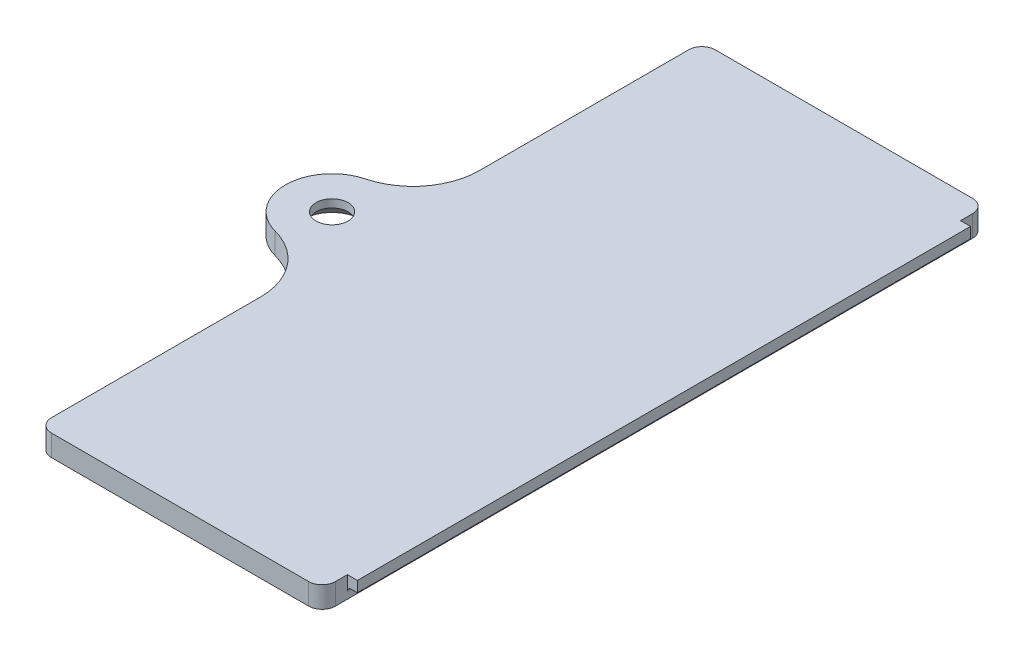
SolidWorks part; units mm, degrees
ref_plane "Front Plane" through (0, 0, 0) normal (0, 0, 1) x (1, 0, 0)
ref_plane "Top Plane" through (0, 0, 0) normal (0, 1, 0) x (1, 0, 0)
ref_plane "Right Plane" through (0, 0, 0) normal (1, 0, 0) x (0, 0, -1)
sketch "Door Plate 1.6 + screw ear (R5 / R3.5) Sketch" plane through (0, 0, 0) normal (0, 1, 0) x (1, 0, 0)
  line L0 (9.35, 15.1) -> (30.65, 15.1)
  line L1 (30.65, 15.1) -> (30.65, 64.9)
  line L2 (30.65, 64.9) -> (9.35, 64.9)
  line L3 (9.35, 64.9) -> (9.35, 48.2236)
  line L4 (9.35, 31.7764) -> (9.35, 15.1)
  arc A0 (9.35, 31.7764) -> (5.6147, 36.6138) centre (4.35, 31.7764) ccw
  arc A1 (5.6147, 36.6138) -> (5.6147, 43.3862) centre (6.5, 40) cw
  arc A2 (5.6147, 43.3862) -> (9.35, 48.2236) centre (4.35, 48.2236) ccw
extrude "Door Plate 1.6 + screw ear (R5 / R3.5)" add sketch "Door Plate 1.6 + screw ear (R5 / R3.5) Sketch" along normal blind 1.6
ref_plane "Hook Flange Plane y0.8" through (0, 0.8, 0) normal (0, 1, 0) x (1, 0, 0)
sketch "Hook Flange 0.75 x 0.8 (inner-face plane) Sketch" plane through (0, 0.8, 0) normal (0, 1, 0) x (1, 0, 0)
  line L0 (30.5, 17) -> (31.4, 17)
  line L1 (31.4, 17) -> (31.4, 63)
  line L2 (31.4, 63) -> (30.5, 63)
  line L3 (30.5, 63) -> (30.5, 17)
extrude "Hook Flange 0.75 x 0.8 (inner-face plane)" add sketch "Hook Flange 0.75 x 0.8 (inner-face plane) Sketch" along normal blind 0.8
sketch "Screw Hole 2.4 (free) Sketch" plane through (0, 0, 0) normal (0, 1, 0) x (1, 0, 0)
  circle A0 centre (6.5, 40) radius 1.2
extrude "Screw Hole 2.4 (free)" cut sketch "Screw Hole 2.4 (free) Sketch" along normal through all
chamfer "Screw CSK 90deg (M2)" distance 1 angle 45 1 edges at (6.5, 0, -38.8)
fillet "Door Corners R1 (print)" radius 1 4 edges at (9.35, 0.8, -64.9) (30.65, 0.8, -64.9) (30.65, 0.8, -15.1) (9.35, 0.8, -15.1)
fillet "Hook Flange Root Fillet R0.3" radius 0.3 1 edges at (30.65, 0.8, -40)
sketch "Door Text Slits 8160749347 + TIMER REMOTE (outer face, 0.84 stroke) Sketch" plane through (0, 0, 0) normal (0, 1, 0) x (1, 0, 0)
  line L0 (27.28, 17.22) -> (21.12, 17.22)
  line L1 (20.6, 17.74) -> (20.6, 20.5)
  line L2 (21.12, 21.02) -> (27.28, 21.02)
  line L3 (27.8, 20.5) -> (27.8, 17.74)
  line L4 (21.12, 17.32) -> (27.28, 17.32)
  line L5 (27.7, 17.74) -> (27.7, 20.5)
  line L6 (27.28, 20.92) -> (21.12, 20.92)
  line L7 (20.7, 20.5) -> (20.7, 17.74)
  line L8 (21.12, 24.28) -> (27.28, 24.28)
  line L9 (27.8, 23.76) -> (27.8, 22.76)
  line L10 (26.76, 22.76) -> (26.76, 23.24)
  line L11 (26.76, 23.24) -> (21.12, 23.24)
  line L12 (27.7, 23.76) -> (27.7, 22.76)
  line L13 (26.86, 22.76) -> (26.86, 23.34)
  line L14 (26.86, 23.34) -> (21.12, 23.34)
  line L15 (21.12, 24.18) -> (27.28, 24.18)
  line L16 (21.12, 30.3) -> (24.2, 30.3)
  line L17 (24.72, 29.78) -> (24.72, 27.54)
  line L18 (24.72, 27.54) -> (26.76, 27.54)
  line L19 (26.76, 27.54) -> (26.76, 29.78)
  line L20 (27.8, 29.78) -> (27.8, 27.02)
  line L21 (27.28, 26.5) -> (21.12, 26.5)
  line L22 (20.6, 27.02) -> (20.6, 29.78)
  line L23 (27.7, 29.78) -> (27.7, 27.02)
  line L24 (27.28, 26.6) -> (21.12, 26.6)
  line L25 (20.7, 27.02) -> (20.7, 29.78)
  line L26 (21.12, 30.2) -> (24.2, 30.2)
  line L27 (24.62, 29.78) -> (24.62, 27.44)
  line L28 (24.62, 27.44) -> (26.86, 27.44)
  line L29 (26.86, 27.44) -> (26.86, 29.78)
  line L30 (27.28, 31.14) -> (21.12, 31.14)
  line L31 (20.6, 31.66) -> (20.6, 34.42)
  line L32 (21.12, 34.94) -> (27.28, 34.94)
  line L33 (27.8, 34.42) -> (27.8, 31.66)
  line L34 (21.12, 31.24) -> (27.28, 31.24)
  line L35 (27.7, 31.66) -> (27.7, 34.42)
  line L36 (27.28, 34.84) -> (21.12, 34.84)
  line L37 (20.7, 34.42) -> (20.7, 31.66)
  line L38 (20.9832, 37.8817) -> (27.1432, 39.5617)
  line L39 (27.8, 39.06) -> (27.8, 36.3)
  line L40 (26.76, 36.3) -> (26.76, 38.3792)
  line L41 (26.76, 38.3792) -> (21.2568, 36.8783)
  line L42 (27.7, 39.06) -> (27.7, 36.3)
  line L43 (26.86, 36.3) -> (26.86, 38.5101)
  line L44 (26.86, 38.5101) -> (21.2305, 36.9748)
  line L45 (21.0095, 37.7852) -> (27.1695, 39.4652)
  line L46 (21.12, 44.22) -> (27.28, 44.22)
  line L47 (27.28, 43.18) -> (24.72, 43.18)
  line L48 (24.72, 43.18) -> (24.72, 41.46)
  line L49 (24.72, 41.46) -> (27.28, 41.46)
  line L50 (27.28, 40.42) -> (24.2, 40.42)
  line L51 (23.68, 40.94) -> (23.68, 43.18)
  line L52 (23.68, 43.18) -> (21.12, 43.18)
  line L53 (27.28, 40.52) -> (24.2, 40.52)
  line L54 (23.78, 40.94) -> (23.78, 43.28)
  line L55 (23.78, 43.28) -> (21.12, 43.28)
  line L56 (21.12, 44.12) -> (27.28, 44.12)
  line L57 (27.28, 43.28) -> (24.62, 43.28)
  line L58 (24.62, 43.28) -> (24.62, 41.36)
  line L59 (24.62, 41.36) -> (27.28, 41.36)
  line L60 (23.68, 47.82) -> (21.64, 47.82)
  line L61 (21.64, 47.82) -> (21.64, 45.58)
  line L62 (20.6, 45.58) -> (20.6, 48.34)
  line L63 (21.12, 48.86) -> (27.28, 48.86)
  line L64 (27.8, 48.34) -> (27.8, 45.58)
  line L65 (27.28, 45.06) -> (24.2, 45.06)
  line L66 (23.68, 45.58) -> (23.68, 47.82)
  line L67 (20.7, 48.34) -> (20.7, 45.58)
  line L68 (21.54, 45.58) -> (21.54, 47.92)
  line L69 (21.54, 47.92) -> (23.78, 47.92)
  line L70 (23.78, 47.92) -> (23.78, 45.58)
  line L71 (24.2, 45.16) -> (27.28, 45.16)
  line L72 (27.7, 45.58) -> (27.7, 48.34)
  line L73 (27.28, 48.76) -> (21.12, 48.76)
  line L74 (21.64, 52.46) -> (21.64, 50.22)
  line L75 (20.6, 50.22) -> (20.6, 52.98)
  line L76 (21.12, 53.5) -> (27.28, 53.5)
  line L77 (27.8, 52.98) -> (27.8, 50.22)
  line L78 (26.76, 50.22) -> (26.76, 52.46)
  line L79 (26.76, 52.46) -> (24.72, 52.46)
  line L80 (24.72, 52.46) -> (24.72, 51.02)
  line L81 (23.68, 51.02) -> (23.68, 52.46)
  line L82 (23.68, 52.46) -> (21.64, 52.46)
  line L83 (27.28, 53.4) -> (21.12, 53.4)
  line L84 (20.7, 52.98) -> (20.7, 50.22)
  line L85 (21.54, 50.22) -> (21.54, 52.56)
  line L86 (21.54, 52.56) -> (23.78, 52.56)
  line L87 (23.78, 52.56) -> (23.78, 51.02)
  line L88 (24.62, 51.02) -> (24.62, 52.56)
  line L89 (24.62, 52.56) -> (26.86, 52.56)
  line L90 (26.86, 52.56) -> (26.86, 50.22)
  line L91 (27.7, 50.22) -> (27.7, 52.98)
  line L92 (21.12, 58.14) -> (27.28, 58.14)
  line L93 (27.28, 57.1) -> (24.72, 57.1)
  line L94 (24.72, 57.1) -> (24.72, 55.38)
  line L95 (24.72, 55.38) -> (27.28, 55.38)
  line L96 (27.28, 54.34) -> (24.2, 54.34)
  line L97 (23.68, 54.86) -> (23.68, 57.1)
  line L98 (23.68, 57.1) -> (21.12, 57.1)
  line L99 (27.28, 54.44) -> (24.2, 54.44)
  line L100 (23.78, 54.86) -> (23.78, 57.2)
  line L101 (23.78, 57.2) -> (21.12, 57.2)
  line L102 (21.12, 58.04) -> (27.28, 58.04)
  line L103 (27.28, 57.2) -> (24.62, 57.2)
  line L104 (24.62, 57.2) -> (24.62, 55.28)
  line L105 (24.62, 55.28) -> (27.28, 55.28)
  line L106 (20.9832, 61.0817) -> (27.1432, 62.7617)
  line L107 (27.8, 62.26) -> (27.8, 59.5)
  line L108 (26.76, 59.5) -> (26.76, 61.5792)
  line L109 (26.76, 61.5792) -> (21.2568, 60.0783)
  line L110 (27.7, 62.26) -> (27.7, 59.5)
  line L111 (26.86, 59.5) -> (26.86, 61.7101)
  line L112 (26.86, 61.7101) -> (21.2305, 60.1748)
  line L113 (21.0095, 60.9852) -> (27.1695, 62.6652)
  line L114 (14.12, 18.04) -> (17.76, 18.04)
  line L115 (17.76, 18.04) -> (17.76, 17.58)
  line L116 (18.8, 17.58) -> (18.8, 19.54)
  line L117 (17.76, 19.54) -> (17.76, 19.08)
  line L118 (17.76, 19.08) -> (14.12, 19.08)
  line L119 (18.7, 17.58) -> (18.7, 19.54)
  line L120 (17.86, 19.54) -> (17.86, 18.98)
  line L121 (17.86, 18.98) -> (14.12, 18.98)
  line L122 (14.12, 18.14) -> (17.86, 18.14)
  line L123 (17.86, 18.14) -> (17.86, 17.58)
  line L124 (18.28, 20.9) -> (14.12, 20.9)
  line L125 (14.12, 21.94) -> (18.28, 21.94)
  line L126 (14.12, 21.84) -> (18.28, 21.84)
  line L127 (18.28, 21) -> (14.12, 21)
  line L128 (17.76, 26.54) -> (14.12, 26.54)
  line L129 (14.12, 27.58) -> (18.28, 27.58)
  line L130 (18.8, 27.06) -> (18.8, 23.3)
  line L131 (18.28, 22.78) -> (14.12, 22.78)
  line L132 (14.12, 23.82) -> (17.76, 23.82)
  line L133 (17.76, 23.82) -> (17.76, 24.66)
  line L134 (17.76, 24.66) -> (15.9, 24.66)
  line L135 (15.9, 25.7) -> (17.76, 25.7)
  line L136 (17.76, 25.7) -> (17.76, 26.54)
  line L137 (18.7, 23.3) -> (18.7, 27.06)
  line L138 (18.28, 27.48) -> (14.12, 27.48)
  line L139 (14.12, 26.64) -> (17.86, 26.64)
  line L140 (17.86, 26.64) -> (17.86, 25.6)
  line L141 (17.86, 25.6) -> (15.9, 25.6)
  line L142 (15.9, 24.76) -> (17.86, 24.76)
  line L143 (17.86, 24.76) -> (17.86, 23.72)
  line L144 (17.86, 23.72) -> (14.12, 23.72)
  line L145 (14.12, 22.88) -> (18.28, 22.88)
  line L146 (14.64, 30.5) -> (14.64, 29.46)
  line L147 (14.64, 29.46) -> (15.68, 29.46)
  line L148 (15.68, 29.46) -> (15.68, 30.2)
  line L149 (16.72, 30.2) -> (16.72, 29.46)
  line L150 (16.72, 29.46) -> (17.76, 29.46)
  line L151 (17.76, 29.46) -> (17.76, 30.5)
  line L152 (18.8, 30.5) -> (18.8, 28.94)
  line L153 (18.28, 28.42) -> (14.12, 28.42)
  line L154 (13.6, 28.94) -> (13.6, 30.5)
  line L155 (18.7, 30.5) -> (18.7, 28.94)
  line L156 (18.28, 28.52) -> (14.12, 28.52)
  line L157 (13.7, 28.94) -> (13.7, 30.5)
  line L158 (14.54, 30.5) -> (14.54, 29.36)
  line L159 (14.54, 29.36) -> (15.78, 29.36)
  line L160 (15.78, 29.36) -> (15.78, 30.2)
  line L161 (16.62, 30.2) -> (16.62, 29.36)
  line L162 (16.62, 29.36) -> (17.86, 29.36)
  line L163 (17.86, 29.36) -> (17.86, 30.5)
  line L164 (15.68, 35.14) -> (15.68, 35.0446)
  line L165 (15.68, 35.0446) -> (14.3226, 35.6189)
  line L166 (13.9174, 34.6611) -> (15.68, 33.9154)
  line L167 (15.68, 33.9154) -> (15.68, 32.9)
  line L168 (15.68, 32.9) -> (14.12, 32.9)
  line L169 (14.12, 31.86) -> (18.28, 31.86)
  line L170 (18.8, 32.38) -> (18.8, 35.14)
  line L171 (18.28, 35.66) -> (16.2, 35.66)
  line L172 (14.12, 31.96) -> (18.28, 31.96)
  line L173 (18.7, 32.38) -> (18.7, 35.14)
  line L174 (18.28, 35.56) -> (16.2, 35.56)
  line L175 (15.78, 35.14) -> (15.78, 34.8937)
  line L176 (15.78, 34.8937) -> (14.2836, 35.5268)
  line L177 (13.9564, 34.7532) -> (15.78, 33.9817)
  line L178 (15.78, 33.9817) -> (15.78, 32.8)
  line L179 (15.78, 32.8) -> (14.12, 32.8)
  line L180 (15.68, 42.22) -> (15.68, 42.1246)
  line L181 (15.68, 42.1246) -> (14.3226, 42.6989)
  line L182 (13.9174, 41.7411) -> (15.68, 40.9954)
  line L183 (15.68, 40.9954) -> (15.68, 39.98)
  line L184 (15.68, 39.98) -> (14.12, 39.98)
  line L185 (14.12, 38.94) -> (18.28, 38.94)
  line L186 (18.8, 39.46) -> (18.8, 42.22)
  line L187 (18.28, 42.74) -> (16.2, 42.74)
  line L188 (14.12, 39.04) -> (18.28, 39.04)
  line L189 (18.7, 39.46) -> (18.7, 42.22)
  line L190 (18.28, 42.64) -> (16.2, 42.64)
  line L191 (15.78, 42.22) -> (15.78, 41.9737)
  line L192 (15.78, 41.9737) -> (14.2836, 42.6068)
  line L193 (13.9564, 41.8332) -> (15.78, 41.0617)
  line L194 (15.78, 41.0617) -> (15.78, 39.88)
  line L195 (15.78, 39.88) -> (14.12, 39.88)
  line L196 (14.64, 45.66) -> (14.64, 44.62)
  line L197 (14.64, 44.62) -> (15.68, 44.62)
  line L198 (15.68, 44.62) -> (15.68, 45.36)
  line L199 (16.72, 45.36) -> (16.72, 44.62)
  line L200 (16.72, 44.62) -> (17.76, 44.62)
  line L201 (17.76, 44.62) -> (17.76, 45.66)
  line L202 (18.8, 45.66) -> (18.8, 44.1)
  line L203 (18.28, 43.58) -> (14.12, 43.58)
  line L204 (13.6, 44.1) -> (13.6, 45.66)
  line L205 (18.7, 45.66) -> (18.7, 44.1)
  line L206 (18.28, 43.68) -> (14.12, 43.68)
  line L207 (13.7, 44.1) -> (13.7, 45.66)
  line L208 (14.54, 45.66) -> (14.54, 44.52)
  line L209 (14.54, 44.52) -> (15.78, 44.52)
  line L210 (15.78, 44.52) -> (15.78, 45.36)
  line L211 (16.62, 45.36) -> (16.62, 44.52)
  line L212 (16.62, 44.52) -> (17.86, 44.52)
  line L213 (17.86, 44.52) -> (17.86, 45.66)
  line L214 (17.76, 50.78) -> (14.12, 50.78)
  line L215 (14.12, 51.82) -> (18.28, 51.82)
  line L216 (18.8, 51.3) -> (18.8, 47.54)
  line L217 (18.28, 47.02) -> (14.12, 47.02)
  line L218 (14.12, 48.06) -> (17.76, 48.06)
  line L219 (17.76, 48.06) -> (17.76, 48.9)
  line L220 (17.76, 48.9) -> (15.9, 48.9)
  line L221 (15.9, 49.94) -> (17.76, 49.94)
  line L222 (17.76, 49.94) -> (17.76, 50.78)
  line L223 (18.7, 47.54) -> (18.7, 51.3)
  line L224 (18.28, 51.72) -> (14.12, 51.72)
  line L225 (14.12, 50.88) -> (17.86, 50.88)
  line L226 (17.86, 50.88) -> (17.86, 49.84)
  line L227 (17.86, 49.84) -> (15.9, 49.84)
  line L228 (15.9, 49) -> (17.86, 49)
  line L229 (17.86, 49) -> (17.86, 47.96)
  line L230 (17.86, 47.96) -> (14.12, 47.96)
  line L231 (14.12, 47.12) -> (18.28, 47.12)
  line L232 (18.28, 52.66) -> (14.12, 52.66)
  line L233 (13.6, 53.18) -> (13.6, 55.14)
  line L234 (14.12, 55.66) -> (18.28, 55.66)
  line L235 (18.8, 55.14) -> (18.8, 53.18)
  line L236 (14.12, 52.76) -> (18.28, 52.76)
  line L237 (18.7, 53.18) -> (18.7, 55.14)
  line L238 (18.28, 55.56) -> (14.12, 55.56)
  line L239 (13.7, 55.14) -> (13.7, 53.18)
  line L240 (14.12, 57.48) -> (17.76, 57.48)
  line L241 (17.76, 57.48) -> (17.76, 57.02)
  line L242 (18.8, 57.02) -> (18.8, 58.98)
  line L243 (17.76, 58.98) -> (17.76, 58.52)
  line L244 (17.76, 58.52) -> (14.12, 58.52)
  line L245 (18.7, 57.02) -> (18.7, 58.98)
  line L246 (17.86, 58.98) -> (17.86, 58.42)
  line L247 (17.86, 58.42) -> (14.12, 58.42)
  line L248 (14.12, 57.58) -> (17.86, 57.58)
  line L249 (17.86, 57.58) -> (17.86, 57.02)
  line L250 (14.64, 62.42) -> (14.64, 61.38)
  line L251 (14.64, 61.38) -> (15.68, 61.38)
  line L252 (15.68, 61.38) -> (15.68, 62.12)
  line L253 (16.72, 62.12) -> (16.72, 61.38)
  line L254 (16.72, 61.38) -> (17.76, 61.38)
  line L255 (17.76, 61.38) -> (17.76, 62.42)
  line L256 (18.8, 62.42) -> (18.8, 60.86)
  line L257 (18.28, 60.34) -> (14.12, 60.34)
  line L258 (13.6, 60.86) -> (13.6, 62.42)
  line L259 (18.7, 62.42) -> (18.7, 60.86)
  line L260 (18.28, 60.44) -> (14.12, 60.44)
  line L261 (13.7, 60.86) -> (13.7, 62.42)
  line L262 (14.54, 62.42) -> (14.54, 61.28)
  line L263 (14.54, 61.28) -> (15.78, 61.28)
  line L264 (15.78, 61.28) -> (15.78, 62.12)
  line L265 (16.62, 62.12) -> (16.62, 61.28)
  line L266 (16.62, 61.28) -> (17.86, 61.28)
  line L267 (17.86, 61.28) -> (17.86, 62.42)
  arc A0 (27.8, 17.74) -> (27.28, 17.22) centre (27.28, 17.74) cw
  arc A1 (21.12, 17.22) -> (20.6, 17.74) centre (21.12, 17.74) cw
  arc A2 (20.6, 20.5) -> (21.12, 21.02) centre (21.12, 20.5) cw
  arc A3 (27.28, 21.02) -> (27.8, 20.5) centre (27.28, 20.5) cw
  arc A4 (20.7, 17.74) -> (21.12, 17.32) centre (21.12, 17.74) ccw
  arc A5 (27.28, 17.32) -> (27.7, 17.74) centre (27.28, 17.74) ccw
  arc A6 (27.7, 20.5) -> (27.28, 20.92) centre (27.28, 20.5) ccw
  arc A7 (21.12, 20.92) -> (20.7, 20.5) centre (21.12, 20.5) ccw
  arc A8 (21.12, 23.24) -> (21.12, 24.28) centre (21.12, 23.76) cw
  arc A9 (27.28, 24.28) -> (27.8, 23.76) centre (27.28, 23.76) cw
  arc A10 (27.8, 22.76) -> (26.76, 22.76) centre (27.28, 22.76) cw
  arc A11 (27.7, 22.76) -> (26.86, 22.76) centre (27.28, 22.76) cw
  arc A12 (21.12, 23.34) -> (21.12, 24.18) centre (21.12, 23.76) cw
  arc A13 (27.28, 24.18) -> (27.7, 23.76) centre (27.28, 23.76) cw
  arc A14 (20.6, 29.78) -> (21.12, 30.3) centre (21.12, 29.78) cw
  arc A15 (24.2, 30.3) -> (24.72, 29.78) centre (24.2, 29.78) cw
  arc A16 (26.76, 29.78) -> (27.8, 29.78) centre (27.28, 29.78) cw
  arc A17 (27.8, 27.02) -> (27.28, 26.5) centre (27.28, 27.02) cw
  arc A18 (21.12, 26.5) -> (20.6, 27.02) centre (21.12, 27.02) cw
  arc A19 (26.86, 29.78) -> (27.7, 29.78) centre (27.28, 29.78) cw
  arc A20 (27.7, 27.02) -> (27.28, 26.6) centre (27.28, 27.02) cw
  arc A21 (21.12, 26.6) -> (20.7, 27.02) centre (21.12, 27.02) cw
  arc A22 (20.7, 29.78) -> (21.12, 30.2) centre (21.12, 29.78) cw
  arc A23 (24.2, 30.2) -> (24.62, 29.78) centre (24.2, 29.78) cw
  arc A24 (27.8, 31.66) -> (27.28, 31.14) centre (27.28, 31.66) cw
  arc A25 (21.12, 31.14) -> (20.6, 31.66) centre (21.12, 31.66) cw
  arc A26 (20.6, 34.42) -> (21.12, 34.94) centre (21.12, 34.42) cw
  arc A27 (27.28, 34.94) -> (27.8, 34.42) centre (27.28, 34.42) cw
  arc A28 (20.7, 31.66) -> (21.12, 31.24) centre (21.12, 31.66) ccw
  arc A29 (27.28, 31.24) -> (27.7, 31.66) centre (27.28, 31.66) ccw
  arc A30 (27.7, 34.42) -> (27.28, 34.84) centre (27.28, 34.42) ccw
  arc A31 (21.12, 34.84) -> (20.7, 34.42) centre (21.12, 34.42) ccw
  arc A32 (21.2568, 36.8783) -> (20.9832, 37.8817) centre (21.12, 37.38) cw
  arc A33 (27.1432, 39.5617) -> (27.8, 39.06) centre (27.28, 39.06) cw
  arc A34 (27.8, 36.3) -> (26.76, 36.3) centre (27.28, 36.3) cw
  arc A35 (27.7, 36.3) -> (26.86, 36.3) centre (27.28, 36.3) cw
  arc A36 (21.2305, 36.9748) -> (21.0095, 37.7852) centre (21.12, 37.38) cw
  arc A37 (27.1695, 39.4652) -> (27.7, 39.06) centre (27.28, 39.06) cw
  arc A38 (21.12, 43.18) -> (21.12, 44.22) centre (21.12, 43.7) cw
  arc A39 (27.28, 44.22) -> (27.8, 43.7) centre (27.28, 43.7) cw
  arc A40 (27.8, 43.7) -> (27.28, 43.18) centre (27.28, 43.7) cw
  arc A41 (27.28, 41.46) -> (27.8, 40.94) centre (27.28, 40.94) cw
  arc A42 (27.8, 40.94) -> (27.28, 40.42) centre (27.28, 40.94) cw
  arc A43 (24.2, 40.42) -> (23.68, 40.94) centre (24.2, 40.94) cw
  arc A44 (27.28, 41.36) -> (27.7, 40.94) centre (27.28, 40.94) cw
  arc A45 (27.7, 40.94) -> (27.28, 40.52) centre (27.28, 40.94) cw
  arc A46 (24.2, 40.52) -> (23.78, 40.94) centre (24.2, 40.94) cw
  arc A47 (21.12, 43.28) -> (21.12, 44.12) centre (21.12, 43.7) cw
  arc A48 (27.28, 44.12) -> (27.7, 43.7) centre (27.28, 43.7) cw
  arc A49 (27.7, 43.7) -> (27.28, 43.28) centre (27.28, 43.7) cw
  arc A50 (21.64, 45.58) -> (20.6, 45.58) centre (21.12, 45.58) cw
  arc A51 (20.6, 48.34) -> (21.12, 48.86) centre (21.12, 48.34) cw
  arc A52 (27.28, 48.86) -> (27.8, 48.34) centre (27.28, 48.34) cw
  arc A53 (27.8, 45.58) -> (27.28, 45.06) centre (27.28, 45.58) cw
  arc A54 (24.2, 45.06) -> (23.68, 45.58) centre (24.2, 45.58) cw
  arc A55 (21.12, 48.76) -> (20.7, 48.34) centre (21.12, 48.34) ccw
  arc A56 (20.7, 45.58) -> (21.54, 45.58) centre (21.12, 45.58) ccw
  arc A57 (23.78, 45.58) -> (24.2, 45.16) centre (24.2, 45.58) ccw
  arc A58 (27.28, 45.16) -> (27.7, 45.58) centre (27.28, 45.58) ccw
  arc A59 (27.7, 48.34) -> (27.28, 48.76) centre (27.28, 48.34) ccw
  arc A60 (21.64, 50.22) -> (20.6, 50.22) centre (21.12, 50.22) cw
  arc A61 (20.6, 52.98) -> (21.12, 53.5) centre (21.12, 52.98) cw
  arc A62 (27.28, 53.5) -> (27.8, 52.98) centre (27.28, 52.98) cw
  arc A63 (27.8, 50.22) -> (26.76, 50.22) centre (27.28, 50.22) cw
  arc A64 (24.72, 51.02) -> (23.68, 51.02) centre (24.2, 51.02) cw
  arc A65 (27.7, 52.98) -> (27.28, 53.4) centre (27.28, 52.98) ccw
  arc A66 (21.12, 53.4) -> (20.7, 52.98) centre (21.12, 52.98) ccw
  arc A67 (20.7, 50.22) -> (21.54, 50.22) centre (21.12, 50.22) ccw
  arc A68 (23.78, 51.02) -> (24.62, 51.02) centre (24.2, 51.02) ccw
  arc A69 (26.86, 50.22) -> (27.7, 50.22) centre (27.28, 50.22) ccw
  arc A70 (21.12, 57.1) -> (21.12, 58.14) centre (21.12, 57.62) cw
  arc A71 (27.28, 58.14) -> (27.8, 57.62) centre (27.28, 57.62) cw
  arc A72 (27.8, 57.62) -> (27.28, 57.1) centre (27.28, 57.62) cw
  arc A73 (27.28, 55.38) -> (27.8, 54.86) centre (27.28, 54.86) cw
  arc A74 (27.8, 54.86) -> (27.28, 54.34) centre (27.28, 54.86) cw
  arc A75 (24.2, 54.34) -> (23.68, 54.86) centre (24.2, 54.86) cw
  arc A76 (27.28, 55.28) -> (27.7, 54.86) centre (27.28, 54.86) cw
  arc A77 (27.7, 54.86) -> (27.28, 54.44) centre (27.28, 54.86) cw
  arc A78 (24.2, 54.44) -> (23.78, 54.86) centre (24.2, 54.86) cw
  arc A79 (21.12, 57.2) -> (21.12, 58.04) centre (21.12, 57.62) cw
  arc A80 (27.28, 58.04) -> (27.7, 57.62) centre (27.28, 57.62) cw
  arc A81 (27.7, 57.62) -> (27.28, 57.2) centre (27.28, 57.62) cw
  arc A82 (21.2568, 60.0783) -> (20.9832, 61.0817) centre (21.12, 60.58) cw
  arc A83 (27.1432, 62.7617) -> (27.8, 62.26) centre (27.28, 62.26) cw
  arc A84 (27.8, 59.5) -> (26.76, 59.5) centre (27.28, 59.5) cw
  arc A85 (27.7, 59.5) -> (26.86, 59.5) centre (27.28, 59.5) cw
  arc A86 (21.2305, 60.1748) -> (21.0095, 60.9852) centre (21.12, 60.58) cw
  arc A87 (27.1695, 62.6652) -> (27.7, 62.26) centre (27.28, 62.26) cw
  arc A88 (14.12, 19.08) -> (14.12, 18.04) centre (14.12, 18.56) ccw
  arc A89 (17.76, 17.58) -> (18.8, 17.58) centre (18.28, 17.58) ccw
  arc A90 (18.8, 19.54) -> (17.76, 19.54) centre (18.28, 19.54) ccw
  arc A91 (17.86, 17.58) -> (18.7, 17.58) centre (18.28, 17.58) ccw
  arc A92 (18.7, 19.54) -> (17.86, 19.54) centre (18.28, 19.54) ccw
  arc A93 (14.12, 18.98) -> (14.12, 18.14) centre (14.12, 18.56) ccw
  arc A94 (14.12, 20.9) -> (14.12, 21.94) centre (14.12, 21.42) cw
  arc A95 (18.28, 21.94) -> (18.8, 21.42) centre (18.28, 21.42) cw
  arc A96 (18.8, 21.42) -> (18.28, 20.9) centre (18.28, 21.42) cw
  arc A97 (18.28, 21.84) -> (18.7, 21.42) centre (18.28, 21.42) cw
  arc A98 (18.7, 21.42) -> (18.28, 21) centre (18.28, 21.42) cw
  arc A99 (14.12, 21) -> (14.12, 21.84) centre (14.12, 21.42) cw
  arc A100 (14.12, 26.54) -> (14.12, 27.58) centre (14.12, 27.06) cw
  arc A101 (18.28, 27.58) -> (18.8, 27.06) centre (18.28, 27.06) cw
  arc A102 (18.8, 23.3) -> (18.28, 22.78) centre (18.28, 23.3) cw
  arc A103 (14.12, 22.78) -> (14.12, 23.82) centre (14.12, 23.3) cw
  arc A104 (15.9, 24.66) -> (15.9, 25.7) centre (15.9, 25.18) cw
  arc A105 (18.28, 22.88) -> (18.7, 23.3) centre (18.28, 23.3) ccw
  arc A106 (18.7, 27.06) -> (18.28, 27.48) centre (18.28, 27.06) ccw
  arc A107 (14.12, 27.48) -> (14.12, 26.64) centre (14.12, 27.06) ccw
  arc A108 (15.9, 25.6) -> (15.9, 24.76) centre (15.9, 25.18) ccw
  arc A109 (14.12, 23.72) -> (14.12, 22.88) centre (14.12, 23.3) ccw
  arc A110 (15.68, 30.2) -> (16.72, 30.2) centre (16.2, 30.2) cw
  arc A111 (17.76, 30.5) -> (18.8, 30.5) centre (18.28, 30.5) cw
  arc A112 (18.8, 28.94) -> (18.28, 28.42) centre (18.28, 28.94) cw
  arc A113 (14.12, 28.42) -> (13.6, 28.94) centre (14.12, 28.94) cw
  arc A114 (13.6, 30.5) -> (14.64, 30.5) centre (14.12, 30.5) cw
  arc A115 (17.86, 30.5) -> (18.7, 30.5) centre (18.28, 30.5) cw
  arc A116 (18.7, 28.94) -> (18.28, 28.52) centre (18.28, 28.94) cw
  arc A117 (14.12, 28.52) -> (13.7, 28.94) centre (14.12, 28.94) cw
  arc A118 (13.7, 30.5) -> (14.54, 30.5) centre (14.12, 30.5) cw
  arc A119 (15.78, 30.2) -> (16.62, 30.2) centre (16.2, 30.2) cw
  arc A120 (14.3226, 35.6189) -> (13.9174, 34.6611) centre (14.12, 35.14) ccw
  arc A121 (14.12, 32.9) -> (14.12, 31.86) centre (14.12, 32.38) ccw
  arc A122 (18.28, 31.86) -> (18.8, 32.38) centre (18.28, 32.38) ccw
  arc A123 (18.8, 35.14) -> (18.28, 35.66) centre (18.28, 35.14) ccw
  arc A124 (16.2, 35.66) -> (15.68, 35.14) centre (16.2, 35.14) ccw
  arc A125 (14.12, 32.8) -> (14.12, 31.96) centre (14.12, 32.38) ccw
  arc A126 (18.28, 31.96) -> (18.7, 32.38) centre (18.28, 32.38) ccw
  arc A127 (18.7, 35.14) -> (18.28, 35.56) centre (18.28, 35.14) ccw
  arc A128 (16.2, 35.56) -> (15.78, 35.14) centre (16.2, 35.14) ccw
  arc A129 (14.2836, 35.5268) -> (13.9564, 34.7532) centre (14.12, 35.14) ccw
  arc A130 (14.3226, 42.6989) -> (13.9174, 41.7411) centre (14.12, 42.22) ccw
  arc A131 (14.12, 39.98) -> (14.12, 38.94) centre (14.12, 39.46) ccw
  arc A132 (18.28, 38.94) -> (18.8, 39.46) centre (18.28, 39.46) ccw
  arc A133 (18.8, 42.22) -> (18.28, 42.74) centre (18.28, 42.22) ccw
  arc A134 (16.2, 42.74) -> (15.68, 42.22) centre (16.2, 42.22) ccw
  arc A135 (14.12, 39.88) -> (14.12, 39.04) centre (14.12, 39.46) ccw
  arc A136 (18.28, 39.04) -> (18.7, 39.46) centre (18.28, 39.46) ccw
  arc A137 (18.7, 42.22) -> (18.28, 42.64) centre (18.28, 42.22) ccw
  arc A138 (16.2, 42.64) -> (15.78, 42.22) centre (16.2, 42.22) ccw
  arc A139 (14.2836, 42.6068) -> (13.9564, 41.8332) centre (14.12, 42.22) ccw
  arc A140 (15.68, 45.36) -> (16.72, 45.36) centre (16.2, 45.36) cw
  arc A141 (17.76, 45.66) -> (18.8, 45.66) centre (18.28, 45.66) cw
  arc A142 (18.8, 44.1) -> (18.28, 43.58) centre (18.28, 44.1) cw
  arc A143 (14.12, 43.58) -> (13.6, 44.1) centre (14.12, 44.1) cw
  arc A144 (13.6, 45.66) -> (14.64, 45.66) centre (14.12, 45.66) cw
  arc A145 (17.86, 45.66) -> (18.7, 45.66) centre (18.28, 45.66) cw
  arc A146 (18.7, 44.1) -> (18.28, 43.68) centre (18.28, 44.1) cw
  arc A147 (14.12, 43.68) -> (13.7, 44.1) centre (14.12, 44.1) cw
  arc A148 (13.7, 45.66) -> (14.54, 45.66) centre (14.12, 45.66) cw
  arc A149 (15.78, 45.36) -> (16.62, 45.36) centre (16.2, 45.36) cw
  arc A150 (14.12, 50.78) -> (14.12, 51.82) centre (14.12, 51.3) cw
  arc A151 (18.28, 51.82) -> (18.8, 51.3) centre (18.28, 51.3) cw
  arc A152 (18.8, 47.54) -> (18.28, 47.02) centre (18.28, 47.54) cw
  arc A153 (14.12, 47.02) -> (14.12, 48.06) centre (14.12, 47.54) cw
  arc A154 (15.9, 48.9) -> (15.9, 49.94) centre (15.9, 49.42) cw
  arc A155 (18.28, 47.12) -> (18.7, 47.54) centre (18.28, 47.54) ccw
  arc A156 (18.7, 51.3) -> (18.28, 51.72) centre (18.28, 51.3) ccw
  arc A157 (14.12, 51.72) -> (14.12, 50.88) centre (14.12, 51.3) ccw
  arc A158 (15.9, 49.84) -> (15.9, 49) centre (15.9, 49.42) ccw
  arc A159 (14.12, 47.96) -> (14.12, 47.12) centre (14.12, 47.54) ccw
  arc A160 (18.8, 53.18) -> (18.28, 52.66) centre (18.28, 53.18) cw
  arc A161 (14.12, 52.66) -> (13.6, 53.18) centre (14.12, 53.18) cw
  arc A162 (13.6, 55.14) -> (14.12, 55.66) centre (14.12, 55.14) cw
  arc A163 (18.28, 55.66) -> (18.8, 55.14) centre (18.28, 55.14) cw
  arc A164 (13.7, 53.18) -> (14.12, 52.76) centre (14.12, 53.18) ccw
  arc A165 (18.28, 52.76) -> (18.7, 53.18) centre (18.28, 53.18) ccw
  arc A166 (18.7, 55.14) -> (18.28, 55.56) centre (18.28, 55.14) ccw
  arc A167 (14.12, 55.56) -> (13.7, 55.14) centre (14.12, 55.14) ccw
  arc A168 (14.12, 58.52) -> (14.12, 57.48) centre (14.12, 58) ccw
  arc A169 (17.76, 57.02) -> (18.8, 57.02) centre (18.28, 57.02) ccw
  arc A170 (18.8, 58.98) -> (17.76, 58.98) centre (18.28, 58.98) ccw
  arc A171 (17.86, 57.02) -> (18.7, 57.02) centre (18.28, 57.02) ccw
  arc A172 (18.7, 58.98) -> (17.86, 58.98) centre (18.28, 58.98) ccw
  arc A173 (14.12, 58.42) -> (14.12, 57.58) centre (14.12, 58) ccw
  arc A174 (15.68, 62.12) -> (16.72, 62.12) centre (16.2, 62.12) cw
  arc A175 (17.76, 62.42) -> (18.8, 62.42) centre (18.28, 62.42) cw
  arc A176 (18.8, 60.86) -> (18.28, 60.34) centre (18.28, 60.86) cw
  arc A177 (14.12, 60.34) -> (13.6, 60.86) centre (14.12, 60.86) cw
  arc A178 (13.6, 62.42) -> (14.64, 62.42) centre (14.12, 62.42) cw
  arc A179 (17.86, 62.42) -> (18.7, 62.42) centre (18.28, 62.42) cw
  arc A180 (18.7, 60.86) -> (18.28, 60.44) centre (18.28, 60.86) cw
  arc A181 (14.12, 60.44) -> (13.7, 60.86) centre (14.12, 60.86) cw
  arc A182 (13.7, 62.42) -> (14.54, 62.42) centre (14.12, 62.42) cw
  arc A183 (15.78, 62.12) -> (16.62, 62.12) centre (16.2, 62.12) cw
extrude "Door Text Slits 8160749347 + TIMER REMOTE (outer face, 0.84 stroke)" cut sketch "Door Text Slits 8160749347 + TIMER REMOTE (outer face, 0.84 stroke) Sketch" along normal blind 0.4
sketch "Door Text Counter Slits (outer face) Sketch" plane through (0, 0, 0) normal (0, 1, 0) x (1, 0, 0)
  line L0 (26.86, 18.16) -> (26.86, 20.08)
  line L1 (26.86, 20.08) -> (24.62, 20.08)
  line L2 (24.62, 20.08) -> (24.62, 18.16)
  line L3 (24.62, 18.16) -> (26.86, 18.16)
  line L4 (24.72, 19.98) -> (24.72, 18.26)
  line L5 (24.72, 18.26) -> (26.76, 18.26)
  line L6 (26.76, 18.26) -> (26.76, 19.98)
  line L7 (26.76, 19.98) -> (24.72, 19.98)
  line L8 (21.54, 18.16) -> (23.78, 18.16)
  line L9 (23.78, 18.16) -> (23.78, 20.08)
  line L10 (23.78, 20.08) -> (21.54, 20.08)
  line L11 (21.54, 20.08) -> (21.54, 18.16)
  line L12 (23.68, 19.98) -> (21.64, 19.98)
  line L13 (21.64, 19.98) -> (21.64, 18.26)
  line L14 (21.64, 18.26) -> (23.68, 18.26)
  line L15 (23.68, 18.26) -> (23.68, 19.98)
  line L16 (23.78, 29.36) -> (21.54, 29.36)
  line L17 (21.54, 29.36) -> (21.54, 27.44)
  line L18 (21.54, 27.44) -> (23.78, 27.44)
  line L19 (23.78, 27.44) -> (23.78, 29.36)
  line L20 (21.64, 27.54) -> (23.68, 27.54)
  line L21 (23.68, 27.54) -> (23.68, 29.26)
  line L22 (23.68, 29.26) -> (21.64, 29.26)
  line L23 (21.64, 29.26) -> (21.64, 27.54)
  line L24 (21.54, 32.08) -> (26.86, 32.08)
  line L25 (26.86, 32.08) -> (26.86, 34)
  line L26 (26.86, 34) -> (21.54, 34)
  line L27 (21.54, 34) -> (21.54, 32.08)
  line L28 (26.76, 33.9) -> (21.64, 33.9)
  line L29 (21.64, 33.9) -> (21.64, 32.18)
  line L30 (21.64, 32.18) -> (26.76, 32.18)
  line L31 (26.76, 32.18) -> (26.76, 33.9)
  line L32 (24.62, 46) -> (26.86, 46)
  line L33 (26.86, 46) -> (26.86, 47.92)
  line L34 (26.86, 47.92) -> (24.62, 47.92)
  line L35 (24.62, 47.92) -> (24.62, 46)
  line L36 (26.76, 47.82) -> (24.72, 47.82)
  line L37 (24.72, 47.82) -> (24.72, 46.1)
  line L38 (24.72, 46.1) -> (26.76, 46.1)
  line L39 (26.76, 46.1) -> (26.76, 47.82)
  line L40 (17.86, 32.8) -> (17.86, 34.72)
  line L41 (17.86, 34.72) -> (16.62, 34.72)
  line L42 (16.62, 34.72) -> (16.62, 32.8)
  line L43 (16.62, 32.8) -> (17.86, 32.8)
  line L44 (16.72, 34.62) -> (16.72, 32.9)
  line L45 (16.72, 32.9) -> (17.76, 32.9)
  line L46 (17.76, 32.9) -> (17.76, 34.62)
  line L47 (17.76, 34.62) -> (16.72, 34.62)
  line L48 (17.86, 39.88) -> (17.86, 41.8)
  line L49 (17.86, 41.8) -> (16.62, 41.8)
  line L50 (16.62, 41.8) -> (16.62, 39.88)
  line L51 (16.62, 39.88) -> (17.86, 39.88)
  line L52 (16.72, 41.7) -> (16.72, 39.98)
  line L53 (16.72, 39.98) -> (17.76, 39.98)
  line L54 (17.76, 39.98) -> (17.76, 41.7)
  line L55 (17.76, 41.7) -> (16.72, 41.7)
  line L56 (14.54, 53.6) -> (17.86, 53.6)
  line L57 (17.86, 53.6) -> (17.86, 54.72)
  line L58 (17.86, 54.72) -> (14.54, 54.72)
  line L59 (14.54, 54.72) -> (14.54, 53.6)
  line L60 (17.76, 54.62) -> (14.64, 54.62)
  line L61 (14.64, 54.62) -> (14.64, 53.7)
  line L62 (14.64, 53.7) -> (17.76, 53.7)
  line L63 (17.76, 53.7) -> (17.76, 54.62)
extrude "Door Text Counter Slits (outer face)" cut sketch "Door Text Counter Slits (outer face) Sketch" along normal blind 0.4
